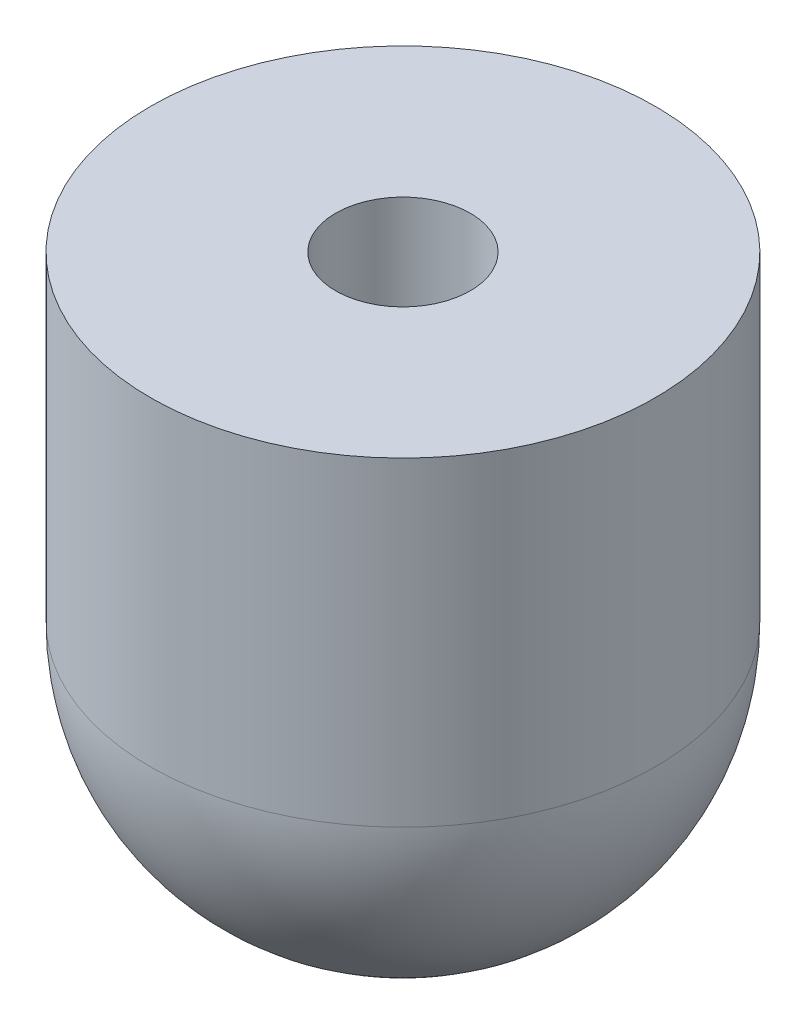
SolidWorks part; units mm, degrees
ref_plane "Front Plane" through (0, 0, 0) normal (0, 0, 1) x (1, 0, 0)
ref_plane "Top Plane" through (0, 0, 0) normal (0, 1, 0) x (1, 0, 0)
ref_plane "Right Plane" through (0, 0, 0) normal (1, 0, 0) x (0, 0, -1)
sketch "Sketch1" plane through (0, 0, 0) normal (0, 0, 1) x (1, 0, 0)
  line L0 (0, 0) -> (-7.5, 0)
  line L1 (-7.5, 0) -> (-7.5, -9.5)
  line L2 (0, 0) -> (0, -17)
  arc A0 (-7.5, -9.5) -> (0, -17) centre (0, -9.5) ccw
  point P6 (0, 0)
  dimension "D1" = 7.5
  dimension "D2" = 9.5
revolve "Revolve1" add sketch "Sketch1" angle 360 about L2
sketch "Sketch2" plane through (0, 0, 0) normal (0, 1, 0) x (1, 0, 0)
  line L1 (3.6, -2.0785) -> (3.6, 2.0785)
  line L2 (3.6, 2.0785) -> (0, 4.1569)
  line L3 (0, 4.1569) -> (-3.6, 2.0785)
  line L4 (-3.6, 2.0785) -> (-3.6, -2.0785)
  line L5 (-3.6, -2.0785) -> (0, -4.1569)
  line L6 (0, -4.1569) -> (3.6, -2.0785)
  circle A0 centre (0, 0) radius 3.6 construction
  point P1 (-3.6, 0)
  point P10 (3.6, 0)
  point P11 (0, 5.3564)
  dimension "D1" = 7.2
extrude "Cut-Extrude1" cut sketch "Sketch2" against normal blind 3.5 from offset 3 offset against normal yes
sketch "Sketch3" plane through (0, 0, 0) normal (0, 1, 0) x (1, 0, 0)
  circle A0 centre (0, 0) radius 2
  dimension "D1" = 4
extrude "Cut-Extrude2" cut sketch "Sketch3" against normal up to next
